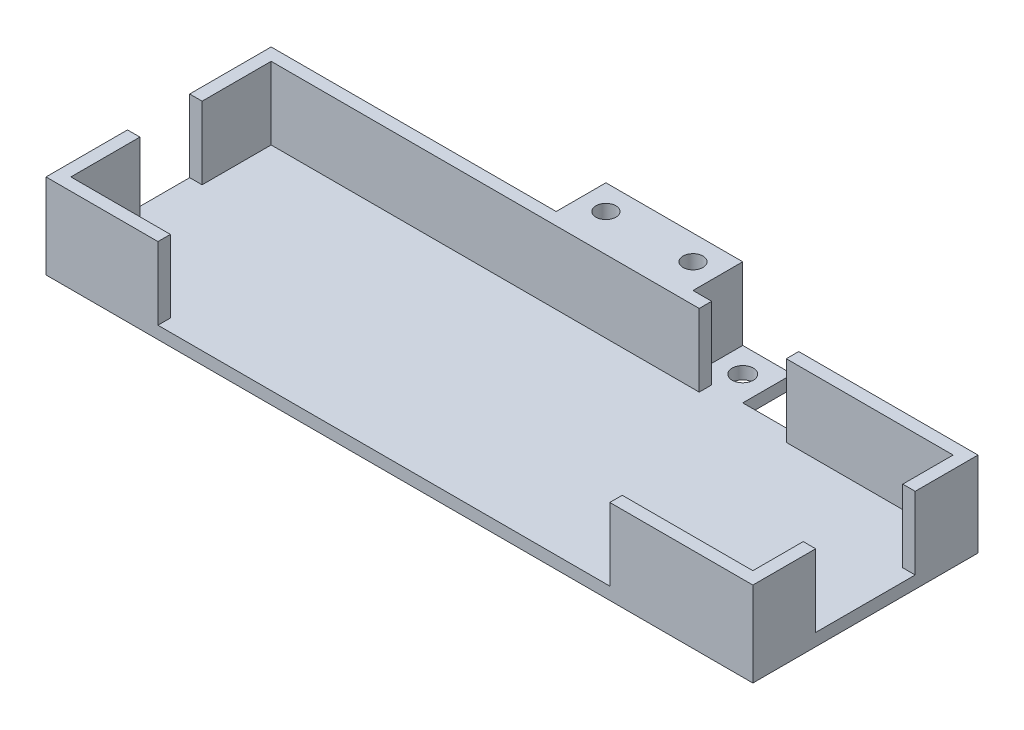
SolidWorks part; units mm, degrees
ref_plane "Front Plane" through (0, 0, 0) normal (0, 0, 1) x (1, 0, 0)
ref_plane "Top Plane" through (0, 0, 0) normal (0, 1, 0) x (1, 0, 0)
ref_plane "Right Plane" through (0, 0, 0) normal (1, 0, 0) x (0, 0, -1)
sketch "Sketch1" plane through (0, 0, 0) normal (0, 1, 0) x (1, 0, 0)
  line L0 (108.65, -1) -> (108.65, 31.2)
  line L1 (0, 0) -> (107.65, 0)
  line L2 (0, 0) -> (0, 30.2)
  line L3 (0, 30.2) -> (107.65, 30.2)
  line L4 (107.65, 0) -> (107.65, 30.2)
  line L5 (-1, 31.2) -> (108.65, 31.2)
  line L6 (-1, -1) -> (-1, 31.2)
  line L7 (-1, -1) -> (108.65, -1)
  line L8 (110.65, -3) -> (110.65, 33.2)
  line L9 (-3, 33.2) -> (110.65, 33.2)
  line L10 (-3, -3) -> (-3, 33.2)
  line L11 (-3, -3) -> (110.65, -3)
  dimension "D1" = 107.65
  dimension "D2" = 30.2
  dimension "D3" = 1
  dimension "D4" = 2
extrude "Boss-Extrude1" add sketch "Sketch1" along normal blind 2 contours L10 L11 L8 L9 L7 L6 L5 L0 | L6 L7 L0 L5 L4 L1 L2 L3 | L1 L4 L3 L2
sketch "Sketch2" plane through (0, 2, 0) normal (0, 1, 0) x (1, 0, 0)
  line L4 (15, -1) -> (15, -3)
  line L5 (-1, 10.1) -> (-1, -1)
  line L6 (-1, 10.1) -> (-3, 10.1)
  line L8 (-1, 20.1) -> (-3, 20.1)
  line L9 (-1, 31.2) -> (-1, -1)
  line L10 (-1, -1) -> (108.65, -1)
  line L11 (108.65, -1) -> (108.65, 31.2)
  line L12 (108.65, 31.2) -> (-1, 31.2)
  line L13 (-1, 31.2) -> (-1, 20.1)
  line L14 (-1, -1) -> (15, -1)
  line L15 (108.65, -1) -> (108.65, 7.1)
  line L16 (108.65, 31.2) -> (-1, 31.2)
  line L18 (87.65, -1) -> (87.65, -3)
  line L19 (87.65, -1) -> (108.65, -1)
  line L20 (110.65, 23.1) -> (110.65, 33.2)
  line L21 (108.65, 7.1) -> (110.65, 7.1)
  line L23 (-3, 33.2) -> (-3, -3)
  line L24 (-3, -3) -> (110.65, -3)
  line L25 (110.65, -3) -> (110.65, 33.2)
  line L26 (110.65, 33.2) -> (-3, 33.2)
  line L27 (-3, 33.2) -> (-3, 20.1)
  line L28 (-3, -3) -> (15, -3)
  line L29 (110.65, -3) -> (110.65, 7.1)
  line L30 (110.65, 33.2) -> (-3, 33.2)
  line L31 (108.65, 23.1) -> (110.65, 23.1)
  line L33 (-3, 10.1) -> (-3, -3)
  line L35 (108.65, 23.1) -> (108.65, 31.2)
  line L36 (87.65, -3) -> (110.65, -3)
  dimension "D2" = 18
  dimension "D4" = 23
  dimension "D1" = 2
  dimension "D3" = 0
extrude "Boss-Extrude2" add sketch "Sketch2" along normal blind 11.65
sketch "Sketch3" plane through (0, 0, 0) normal (0, -1, 0) x (1, 0, 0)
  line L0 (-3, 3) -> (110.65, 3) construction
  line L1 (34.825, 3) -> (72.825, 3) construction
  line L2 (34.825, 3) -> (34.825, 11) construction
  line L3 (34.825, 11) -> (72.825, 11) construction
  line L4 (72.825, 3) -> (72.825, 11) construction
  line L7 (-3, 3) -> (-3, -33.2) construction
  line L8 (-3, -15.1) -> (110.65, -15.1) construction
  line L9 (110.65, 3) -> (110.65, -33.2) construction
  line L10 (72.825, -33.2) -> (72.825, -41.2)
  line L11 (34.825, -41.2) -> (72.825, -41.2)
  line L12 (34.825, -33.2) -> (34.825, -41.2)
  line L13 (34.825, -33.2) -> (72.825, -33.2)
  circle A0 centre (38.825, 7) radius 1.7 construction
  circle A1 centre (68.825, 7) radius 1.7 construction
  circle A2 centre (68.825, -37.2) radius 1.7
  circle A3 centre (38.825, -37.2) radius 1.7
  dimension "D1" = 3.4
  dimension "D2" = 30
  dimension "D3" = 4
  dimension "D5" = 4
  dimension "D4" = 8
  dimension "D6" = 38
  dimension "D7" = 37.825
extrude "Boss-Extrude3" add sketch "Sketch3" against normal blind 2
sketch "Sketch4" plane through (0, 2, 0) normal (0, 1, 0) x (1, 0, 0)
  line L0 (72.825, 33.2) -> (34.825, 33.2) construction
  line L1 (42.825, 33.2) -> (64.825, 33.2)
  line L2 (42.825, 33.2) -> (42.825, 41.2)
  line L3 (42.825, 41.2) -> (64.825, 41.2)
  line L4 (64.825, 33.2) -> (64.825, 41.2)
  line L5 (34.825, 41.2) -> (72.825, 41.2) construction
  line L6 (53.825, 41.2) -> (53.825, 33.2) construction
  circle A0 centre (46.825, 37.2) radius 1.6
  circle A1 centre (38.825, 37.2) radius 1.7 construction
  circle A2 centre (68.825, 37.2) radius 1.7 construction
  circle A3 centre (60.825, 37.2) radius 1.6
  dimension "D1" = 3.2
  dimension "D2" = 4
  dimension "D3" = 4
  dimension "D4" = 4
  dimension "D5" = 4
extrude "Boss-Extrude4" add sketch "Sketch4" along normal blind 11.65
sketch "Sketch5" plane through (0, 13.65, 0) normal (0, 1, 0) x (1, 0, 0)
  line L0 (67.825, 33.2) -> (67.825, 31.2)
  line L1 (110.65, 33.2) -> (64.825, 33.2) construction
  line L2 (-1, 31.2) -> (108.65, 31.2) construction
  line L3 (64.825, 33.2) -> (64.825, 41.2) construction
  line L4 (81.825, 33.2) -> (81.825, 31.2)
  line L5 (64.825, 33.2) -> (64.825, 41.2) construction
  line L6 (67.825, 33.2) -> (81.825, 33.2)
  line L7 (81.825, 31.2) -> (67.825, 31.2)
  dimension "D1" = 3
  dimension "D2" = 17
extrude "Cut-Extrude1" cut sketch "Sketch5" against normal up to surface (11.65 mm away) up to face at (53.2, 2, -10.825)
